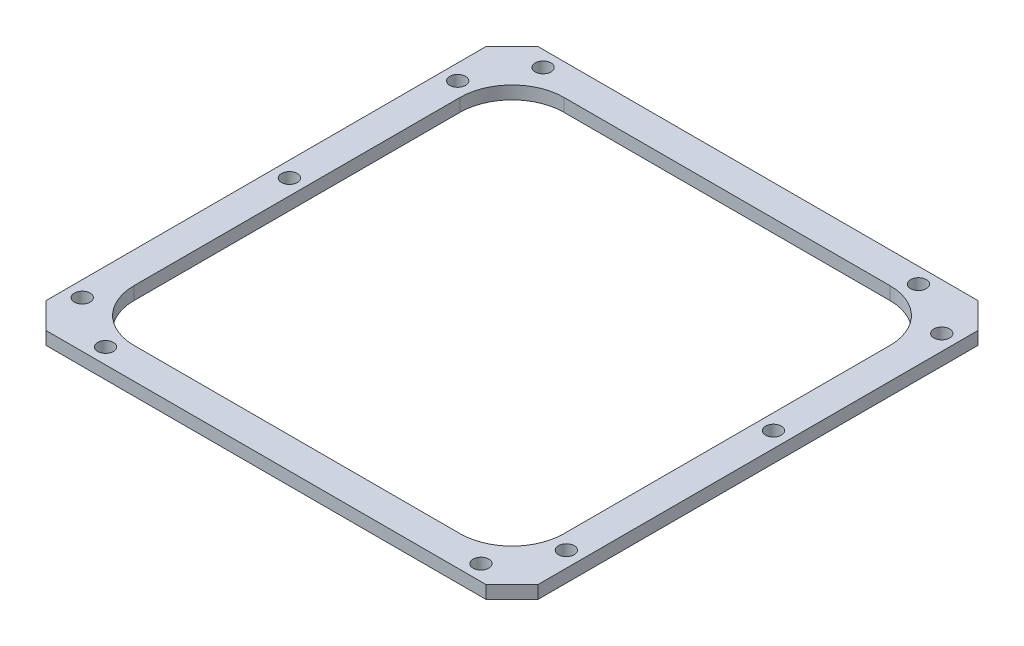
SolidWorks part; units mm, degrees
ref_plane "Front Plane" through (0, 0, 0) normal (0, 0, 1) x (1, 0, 0)
ref_plane "Top Plane" through (0, 0, 0) normal (0, 1, 0) x (1, 0, 0)
ref_plane "Right Plane" through (0, 0, 0) normal (1, 0, 0) x (0, 0, -1)
sketch "Sketch1" plane through (0, 0, 0) normal (0, 1, 0) x (1, 0, 0)
  line L1 (-95, 95) -> (95, 95)
  line L2 (-95, 95) -> (-95, -95)
  line L3 (-95, -95) -> (95, -95)
  line L4 (95, 95) -> (95, -95)
  line L5 (-95, 95) -> (95, -95) construction
  line L6 (-95, -95) -> (95, 95) construction
  point P0 (0, 0)
  dimension "182" = 190
  dimension "D2" = 190
extrude "Boss-Extrude1" add sketch "Sketch1" along normal blind 5 contours L2 L3 L4 L1
sketch "Sketch2" plane through (0, 5, 0) normal (0, 1, 0) x (1, 0, 0)
  line L0 (-95, 95) -> (95, 95) construction
  line L1 (-83, 83) -> (83, 83)
  line L2 (-83, 83) -> (-83, -83)
  line L3 (-83, -83) -> (83, -83)
  line L4 (83, 83) -> (83, -83)
  line L5 (-83, 83) -> (83, -83) construction
  line L6 (-83, -83) -> (83, 83) construction
  line L7 (-95, -95) -> (95, -95) construction
  line L8 (-95, 95) -> (-95, -95) construction
  line L9 (95, 95) -> (95, -95) construction
  point P0 (0, 0)
  dimension "D1" = 12
  dimension "D2" = 12
  dimension "D3" = 12
  dimension "D4" = 12
extrude "Cut-Extrude1" cut sketch "Sketch2" against normal through all
fillet "Fillet1" radius 20 4 edges at (83, 2.5, 83) (-83, 2.5, 83) (-83, 2.5, -83) (83, 2.5, -83)
sketch "Sketch3" plane through (0, 5, 0) normal (0, 1, 0) x (1, 0, 0)
  line L0 (0, 83) -> (0, 95) construction
  line L1 (63, 83) -> (-63, 83) construction
  line L2 (-95, 95) -> (95, 95) construction
  line L3 (-95, 89) -> (95, 89) construction
  line L4 (-95, 95) -> (-95, -95) construction
  line L5 (95, 95) -> (95, -95) construction
  line L9 (95, 89) -> (-95, 89) construction
  line L12 (-95, -95) -> (95, -95) construction
  line L13 (-89, -95) -> (-89, 95) construction
  line L14 (-89, 95) -> (-89, -95) construction
  line L16 (95, -89) -> (-95, -89) construction
  line L17 (-95, -89) -> (95, -89) construction
  line L18 (89, 95) -> (89, -95) construction
  line L19 (89, -95) -> (89, 95) construction
  circle A0 centre (-77, 89) radius 3.05
  circle A1 centre (-89, 68) radius 3.05
  circle A14 centre (77, -89) radius 3.05 [skipped]
  circle A15 centre (89, -68) radius 3.05 [skipped]
  circle A16 centre (-89, -77) radius 3.05 [skipped]
  circle A17 centre (-68, -89) radius 3.05 [skipped]
  circle A18 centre (89, 77) radius 3.05 [skipped]
  circle A19 centre (68, 89) radius 3.05 [skipped]
  circle A22 centre (89, 77) radius 3.05
  circle A23 centre (68, 89) radius 3.05
  circle A26 centre (77, -89) radius 3.05
  circle A27 centre (89, -68) radius 3.05
  circle A30 centre (-89, -77) radius 3.05
  circle A31 centre (-68, -89) radius 3.05
  point P39 (-4, -4)
  point P52 (0, 0)
  point P81 (0, 0)
  dimension "D1" = 6.1
  dimension "D2" = 6.1
  dimension "D3" = 18
  dimension "D4" = 27
  dimension "D5" = 4
  dimension "D10" = 4
extrude "Cut-Extrude2" cut sketch "Sketch3" against normal through all
sketch "Sketch4" plane through (0, 5, 0) normal (0, 1, 0) x (1, 0, 0)
  line L0 (-95, 0) -> (-83, 0) construction
  line L1 (-95, 95) -> (-95, -95) construction
  line L2 (-83, 63) -> (-83, -63) construction
  line L3 (83, 0) -> (95, 0) construction
  line L4 (83, -63) -> (83, 63) construction
  line L5 (95, 95) -> (95, -95) construction
  line L7 (-95, 95) -> (95, 95) construction
  line L8 (-89, 95) -> (-89, -95) construction
  line L9 (-95, -95) -> (95, -95) construction
  line L10 (89, 95) -> (89, -95) construction
  circle A0 centre (-89, 3) radius 3.05
  circle A1 centre (89, 12) radius 3.05
  dimension "D1" = 6.1
  dimension "D3" = 6.1
  dimension "D2" = 98
  dimension "D4" = 9
extrude "Cut-Extrude3" cut sketch "Sketch4" against normal blind 10
chamfer "Chamfer1" distance 10 angle 45 4 edges at (95, 2.5, -95) (-95, 2.5, -95) (-95, 2.5, 95) (95, 2.5, 95)
